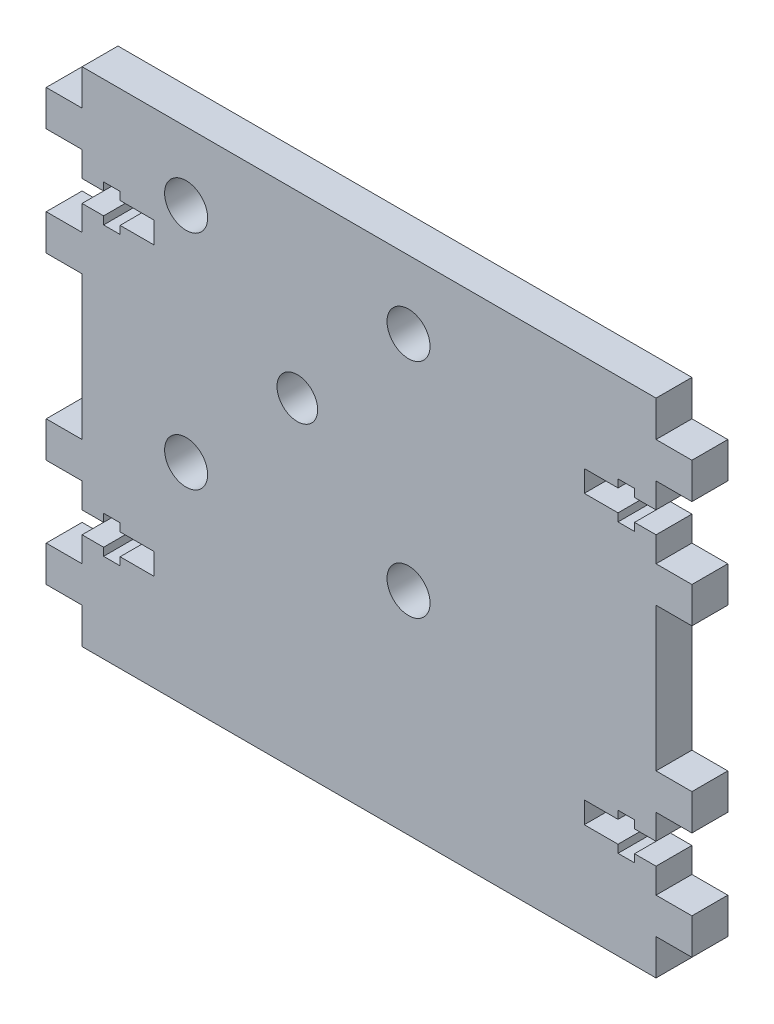
SolidWorks part; units mm, degrees
ref_plane "Front Plane" through (0, 0, 0) normal (0, 0, 1) x (1, 0, 0)
ref_plane "Top Plane" through (0, 0, 0) normal (0, 1, 0) x (1, 0, 0)
ref_plane "Right Plane" through (0, 0, 0) normal (1, 0, 0) x (0, 0, -1)
sketch "Sketch1" plane through (0, 0, 0) normal (0, 0, 1) x (1, 0, 0)
  line L0 (0, 0) -> (0, 70) construction
  line L1 (0, 70) -> (-80, 70)
  line L4 (-40, 38.7693) -> (-40, -40.9046) construction
  line L5 (0, 35) -> (-37.6147, 35) construction
  line L6 (0, 55) -> (-11.2208, 55) construction
  line L7 (0, 53.5) -> (0, 50)
  line L8 (5, 50) -> (5, 45)
  line L9 (5, 45) -> (0, 45)
  line L10 (5, 50) -> (0, 50)
  line L11 (0, 56.5) -> (0, 60)
  line L12 (0, 60) -> (5, 60)
  line L13 (5, 60) -> (5, 65)
  line L14 (5, 65) -> (0, 65)
  line L15 (0, 53.5) -> (0, 56.5) construction
  line L16 (0, 56.5) -> (-3, 56.5)
  line L17 (-5.3, 56.5) -> (-5.3, 57.6)
  line L18 (-3, 52.4) -> (-5.3, 52.4)
  line L19 (-3, 57.6) -> (-3, 56.5)
  line L20 (-5.3, 56.5) -> (-10, 56.5)
  line L21 (-10, 56.5) -> (-10, 53.5)
  line L22 (-10, 53.5) -> (-5.3, 53.5)
  line L23 (-3, 53.5) -> (-3, 52.4)
  line L24 (-5.3, 57.6) -> (-3, 57.6)
  line L25 (-5.3, 52.4) -> (-5.3, 53.5)
  line L26 (-3, 53.5) -> (0, 53.5)
  line L27 (-10, 55) -> (0, 55) construction
  line L66 (-85, 65) -> (-80, 65)
  line L67 (-85, 60) -> (-85, 65)
  line L68 (-80, 60) -> (-85, 60)
  line L69 (-80, 56.5) -> (-80, 60)
  line L70 (-80, 56.5) -> (-77, 56.5)
  line L71 (-77, 57.6) -> (-77, 56.5)
  line L72 (-74.7, 57.6) -> (-77, 57.6)
  line L73 (-74.7, 56.5) -> (-74.7, 57.6)
  line L74 (-74.7, 56.5) -> (-70, 56.5)
  line L75 (-70, 56.5) -> (-70, 53.5)
  line L76 (-70, 53.5) -> (-74.7, 53.5)
  line L77 (-74.7, 52.4) -> (-74.7, 53.5)
  line L78 (-77, 52.4) -> (-74.7, 52.4)
  line L79 (-77, 53.5) -> (-77, 52.4)
  line L80 (-77, 53.5) -> (-80, 53.5)
  line L81 (-80, 53.5) -> (-80, 50)
  line L82 (-85, 50) -> (-80, 50)
  line L83 (-85, 50) -> (-85, 45)
  line L84 (-85, 45) -> (-80, 45)
  line L85 (-80, 70) -> (-80, 65)
  line L90 (0, 65) -> (0, 70)
  line L91 (-85, 25) -> (-80, 25)
  line L92 (-85, 20) -> (-85, 25)
  line L93 (-85, 20) -> (-80, 20)
  line L94 (-80, 16.5) -> (-80, 20)
  line L95 (-77, 16.5) -> (-80, 16.5)
  line L96 (-77, 16.5) -> (-77, 17.6)
  line L97 (-77, 17.6) -> (-74.7, 17.6)
  line L98 (-74.7, 17.6) -> (-74.7, 16.5)
  line L99 (-70, 16.5) -> (-74.7, 16.5)
  line L100 (-70, 13.5) -> (-70, 16.5)
  line L101 (-74.7, 13.5) -> (-70, 13.5)
  line L102 (-74.7, 13.5) -> (-74.7, 12.4)
  line L103 (-74.7, 12.4) -> (-77, 12.4)
  line L104 (-77, 12.4) -> (-77, 13.5)
  line L105 (-80, 13.5) -> (-77, 13.5)
  line L106 (-80, 13.5) -> (-80, 10)
  line L107 (-80, 10) -> (-85, 10)
  line L108 (-85, 10) -> (-85, 5)
  line L109 (-85, 5) -> (-80, 5)
  line L110 (-80, 0) -> (-80, 5)
  line L111 (0, 0) -> (-80, 0)
  line L112 (0, 5) -> (0, 0)
  line L113 (5, 5) -> (0, 5)
  line L114 (5, 10) -> (5, 5)
  line L115 (0, 10) -> (5, 10)
  line L116 (0, 13.5) -> (0, 10)
  line L117 (0, 13.5) -> (-3, 13.5)
  line L118 (-3, 12.4) -> (-3, 13.5)
  line L119 (-5.3, 12.4) -> (-3, 12.4)
  line L120 (-5.3, 13.5) -> (-5.3, 12.4)
  line L121 (-5.3, 13.5) -> (-10, 13.5)
  line L122 (-10, 13.5) -> (-10, 16.5)
  line L123 (-10, 16.5) -> (-5.3, 16.5)
  line L124 (-5.3, 17.6) -> (-5.3, 16.5)
  line L125 (-3, 17.6) -> (-5.3, 17.6)
  line L126 (-3, 16.5) -> (-3, 17.6)
  line L127 (-3, 16.5) -> (0, 16.5)
  line L128 (0, 16.5) -> (0, 20)
  line L129 (5, 20) -> (0, 20)
  line L130 (5, 20) -> (5, 25)
  line L131 (5, 25) -> (0, 25)
  line L132 (-80, 45) -> (-80, 25)
  line L133 (0, 45) -> (0, 25)
  circle A0 centre (-65.5, 60.5) radius 3
  circle A1 centre (-34.5, 60.5) radius 3
  circle A2 centre (-65.5, 29.5) radius 3
  circle A3 centre (-34.5, 29.5) radius 3
  circle A4 centre (-50, 45) radius 2.8353
  circle B0 centre (-65.5, 60.5) radius 1.5
  circle B1 centre (-34.5, 60.5) radius 1.5
  circle B2 centre (-34.5, 29.5) radius 1.5
  circle B3 centre (-65.5, 29.5) radius 1.5
  circle B4 centre (-50, 45) radius 11.5
  line B5 (-34.5, 60.5) -> (-34.5, 29.5) construction
  line B6 (-65.5, 29.5) -> (-65.5, 60.5) construction
  line B7 (-34.5, 29.5) -> (-65.5, 29.5) construction
  line B8 (-65.5, 60.5) -> (-34.5, 60.5) construction
  line B9 (-65.5, 60.5) -> (-34.5, 29.5) construction
  dimension "D16" = 6
  dimension "D2" = 40
  dimension "D3" = 80
  dimension "D4" = 10
  dimension "D5" = 5
  dimension "D6" = 5
  dimension "D7" = 5.2
  dimension "D8" = 3
  dimension "D9" = 2.3
  dimension "D10" = 3
  dimension "D11" = 10
  dimension "D12" = 70
  dimension "D13" = 15
  dimension "D14" = 50
  dimension "D15" = 10
sketch_block_instance "Fixation Nema 17-1"
sketch_block "Fixation Nema 17" parameters "D3"=3, "D4"=23, "D1"=31.844, "D2"=31.844
extrude "Boss-Extrude1" add sketch "Sketch1" along normal blind 5 contours L133 L9 L8 L10 L7 L26 L23 L18 L25 L22 L21 L20 L17 L24 L19 L16 L11 L12 L13 L14 L90 L1 L85 L66 L67 L68 L69 L70 L71 L72 L73 L74 L75 L76 L77 L78 L79 L80 L81 L82 L83 L84 L132 L91 L92 L93 L94 L95 L96 L97 L98 | B4 A4
